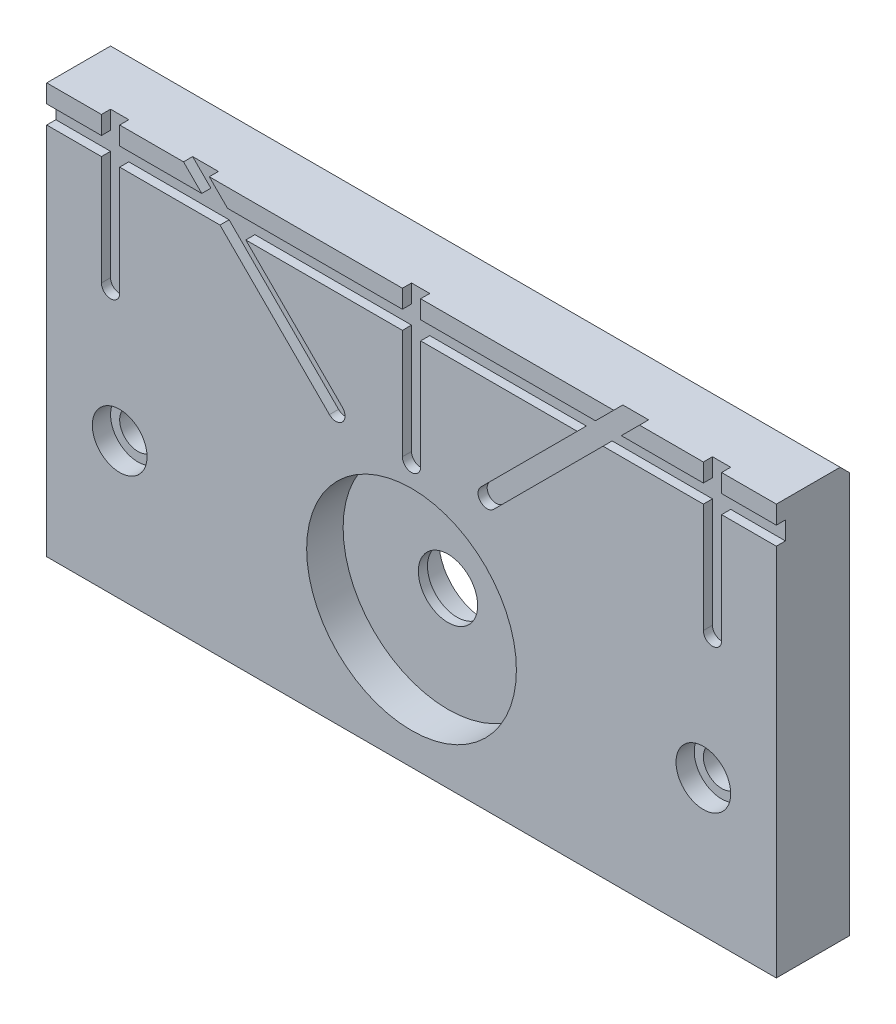
SolidWorks part; units mm, degrees
ref_plane "前视基准面" through (0, 0, 0) normal (0, 0, 1) x (1, 0, 0)
ref_plane "上视基准面" through (0, 0, 0) normal (0, 1, 0) x (1, 0, 0)
ref_plane "右视基准面" through (0, 0, 0) normal (1, 0, 0) x (0, 0, -1)
other "Configuration Table"
ref_plane "基准面1" through (0, 0, 8) normal (0, 0, 1) x (1, 0, 0)
sketch "草图1" plane through (0, 0, 8) normal (0, 0, 1) x (1, 0, 0)
  line L0 (80, -19.1667) -> (80, 40.8333)
  line L1 (80, 40.8333) -> (0, 40.8333)
  line L2 (0, 40.8333) -> (0, -19.1667)
  line L3 (0, -19.1667) -> (80, -19.1667)
  dimension "D1" = 80
  dimension "D2" = 60
extrude "凸台-拉伸1" add sketch "草图1" against normal blind 8
hole_wizard "M3.5 六角头机械螺钉的柱形沉头孔1" positions "草图13" profile "草图12" counterbore size "M3.5" standard "ANSI Metric" end condition through all
sketch "草图13" plane through (0, 0, 8) normal (0, 0, 1) x (1, 0, 0)
  line L1 (0, 10.8333) -> (80, 10.8333) construction
  line L2 (0, 40.8333) -> (0, -19.1667) construction
  line L3 (80, -19.1667) -> (80, 40.8333) construction
  point P0 (8, 10.8333)
  point P1 (72, 10.8333)
  dimension "D1" = 8
  dimension "D2" = 8
sketch "草图12" plane through (8, 10.8333, 8) normal (1, 0, 0) x (0, -1, 0)
  line L0 (0, 0) -> (0, 8)
  line L1 (0, 8) -> (2, 8)
  line L3 (2, 8) -> (2, 2)
  line L4 (2, 2) -> (3, 2)
  line L5 (3, 2) -> (3, 0)
  line L7 (3, 0) -> (0, 0)
  line L11 (0, -6.35) -> (0, 107.95) construction
  dimension "通孔孔直径" = 4
  dimension "通孔孔深度" = 8
  dimension "柱形沉头孔直径" = 6
  dimension "柱形沉头孔深度" = 2
sketch "草图14" plane through (0, 0, 8) normal (0, 0, 1) x (1, 0, 0)
  line L0 (40, 40.8333) -> (40, -19.1667) construction
  line L1 (80, 40.8333) -> (0, 40.8333) construction
  line L2 (0, -19.1667) -> (80, -19.1667) construction
  line L3 (0, 40.8333) -> (0, -19.1667) construction
  line L4 (0, 38.8333) -> (80, 38.8333)
  line L5 (0, 38.8333) -> (0, 36.8333)
  line L6 (0, 36.8333) -> (80, 36.8333)
  line L7 (40, 38.8333) -> (40, 36.8333)
  line L8 (80, -19.1667) -> (80, 40.8333) construction
  line L9 (15, 40.8333) -> (31, 24.8333)
  line L10 (6, 40.8333) -> (8, 40.8333)
  line L11 (6, 40.8333) -> (6, 24.8333)
  line L12 (6, 24.8333) -> (8, 24.8333)
  line L13 (8, 40.8333) -> (8, 24.8333)
  line L18 (39, 40.8333) -> (41, 40.8333)
  line L19 (39, 40.8333) -> (39, 24.8333)
  line L20 (39, 24.8333) -> (41, 24.8333)
  line L21 (40, 40.8333) -> (40, 24.8333)
  line L22 (31, 24.8333) -> (32.4142, 26.2475)
  line L23 (32.4142, 26.2475) -> (16.4142, 42.2475)
  line L24 (16.4142, 42.2475) -> (15, 40.8333)
  line L25 (0, 24.8333) -> (80, 24.8333) construction
  line L26 (74, 24.8333) -> (72, 24.8333)
  line L27 (72, 40.8333) -> (72, 24.8333)
  line L28 (74, 40.8333) -> (72, 40.8333)
  line L29 (74, 40.8333) -> (74, 24.8333)
  line L30 (47.5858, 26.2475) -> (63.5858, 42.2475)
  line L31 (49, 24.8333) -> (47.5858, 26.2475)
  line L32 (65, 40.8333) -> (49, 24.8333)
  line L33 (63.5858, 42.2475) -> (65, 40.8333)
  line L34 (41, 40.8333) -> (41, 24.8333)
  line L35 (80, 38.8333) -> (80, 36.8333)
  dimension "D1" = 2
  dimension "D2" = 2
  dimension "D3" = 6
  dimension "D4" = 2
  dimension "D5" = 16
  dimension "D6" = 2
  dimension "D7" = 1
  dimension "D8" = 7
  dimension "D9" = 45
extrude "切除-拉伸1" cut sketch "草图14" against normal blind 1 contours L4 L35 L6 L5 | L13 L12 L11 L10 | L9 L22 L23 L24 | L19 L20 L34 L18 | L30 L33 L32 L31 | L27 L26 L29 L28
sketch "草图15" plane through (0, 0, 8) normal (0, 0, 1) x (1, 0, 0)
  line L0 (40, 40.8333) -> (40, -19.1667) construction
  line L1 (39, 40.8333) -> (41, 40.8333) construction
  line L2 (0, -19.1667) -> (80, -19.1667) construction
  circle A0 centre (40, 10.8333) radius 3.25
  point P9 (40, 10.8333)
  dimension "D1" = 6.5
extrude "切除-拉伸2" cut sketch "草图15" against normal up to next
sketch "草图17" plane through (0, 0, 8) normal (0, 0, 1) x (1, 0, 0)
  circle A0 centre (40, 10.8333) radius 11.5
  dimension "D1" = 23
extrude "切除-拉伸4" cut sketch "草图17" against normal blind 4
sketch "草图18" plane through (0, 0, 0) normal (0, 0, -1) x (-1, 0, 0)
  circle A0 centre (-40, 10.8333) radius 5
  dimension "D1" = 10
extrude "切除-拉伸5" cut sketch "草图18" against normal blind 3
chamfer "倒角1" distance 1.5 angle 45 2 edges at (74, 10.8333, 0) (10, 10.8333, 0)
chamfer "倒角2" distance 1 angle 45 1 edges at (40, 40.8333, 0)
sketch "草图20" plane through (0, 0, 8) normal (0, 0, 1) x (1, 0, 0)
  line L0 (80, -19.1667) -> (80, 36.8333) construction
  line L1 (0, -19.1667) -> (80, -19.1667)
  line L2 (0, -19.1667) -> (0, -13.1667)
  line L3 (0, -13.1667) -> (80, -13.1667)
  line L4 (80, -19.1667) -> (80, -13.1667)
  dimension "D1" = 6
extrude "切除-拉伸6" cut sketch "草图20" against normal blind 1
sketch "草图21" plane through (0, 0, 7) normal (0, 0, 1) x (1, 0, 0)
  line L0 (80, -19.1667) -> (80, -13.1667) construction
  line L1 (0, -19.1667) -> (80, -19.1667)
  line L2 (0, -19.1667) -> (0, -15.1667)
  line L3 (0, -15.1667) -> (80, -15.1667)
  line L4 (80, -19.1667) -> (80, -15.1667)
  dimension "D1" = 4
extrude "切除-拉伸7" cut sketch "草图21" against normal blind 1
sketch "草图22" plane through (0, 0, 6) normal (0, 0, 1) x (1, 0, 0)
  line L1 (0, -19.1667) -> (80, -19.1667)
  line L2 (0, -19.1667) -> (0, -17.1667)
  line L3 (0, -17.1667) -> (80, -17.1667)
  line L4 (80, -19.1667) -> (80, -17.1667)
  dimension "D1" = 2
extrude "切除-拉伸8" cut sketch "草图22" against normal blind 1
sketch "草图23" plane through (0, 0, 8) normal (0, 0, 1) x (1, 0, 0)
  line L0 (6, 24.8333) -> (8, 24.8333) construction
  line L1 (31, 24.8333) -> (32.4142, 26.2475) construction
  line L2 (39, 24.8333) -> (41, 24.8333) construction
  line L3 (49, 24.8333) -> (47.5858, 26.2475) construction
  line L4 (74, 24.8333) -> (72, 24.8333) construction
  circle A0 centre (7, 24.8333) radius 1
  circle A1 centre (31.7071, 25.5404) radius 1
  circle A2 centre (40, 24.8333) radius 1
  circle A3 centre (48.2929, 25.5404) radius 1
  circle A4 centre (73, 24.8333) radius 1
extrude "切除-拉伸9" cut sketch "草图23" against normal up to surface (1 mm away) up to face at (40, 35.6249, 7)
sketch "草图24" plane through (0, 0, 8) normal (0, 0, 1) x (1, 0, 0)
  line L0 (0, 36.8333) -> (0, -13.1667) construction
  line L1 (0, -4.1667) -> (80, -4.1667)
  line L2 (0, -4.1667) -> (0, -19.1667)
  line L3 (0, -19.1667) -> (80, -19.1667)
  line L4 (80, -4.1667) -> (80, -19.1667)
  dimension "D1" = 15
extrude "切除-拉伸10" cut sketch "草图24" against normal up to next
